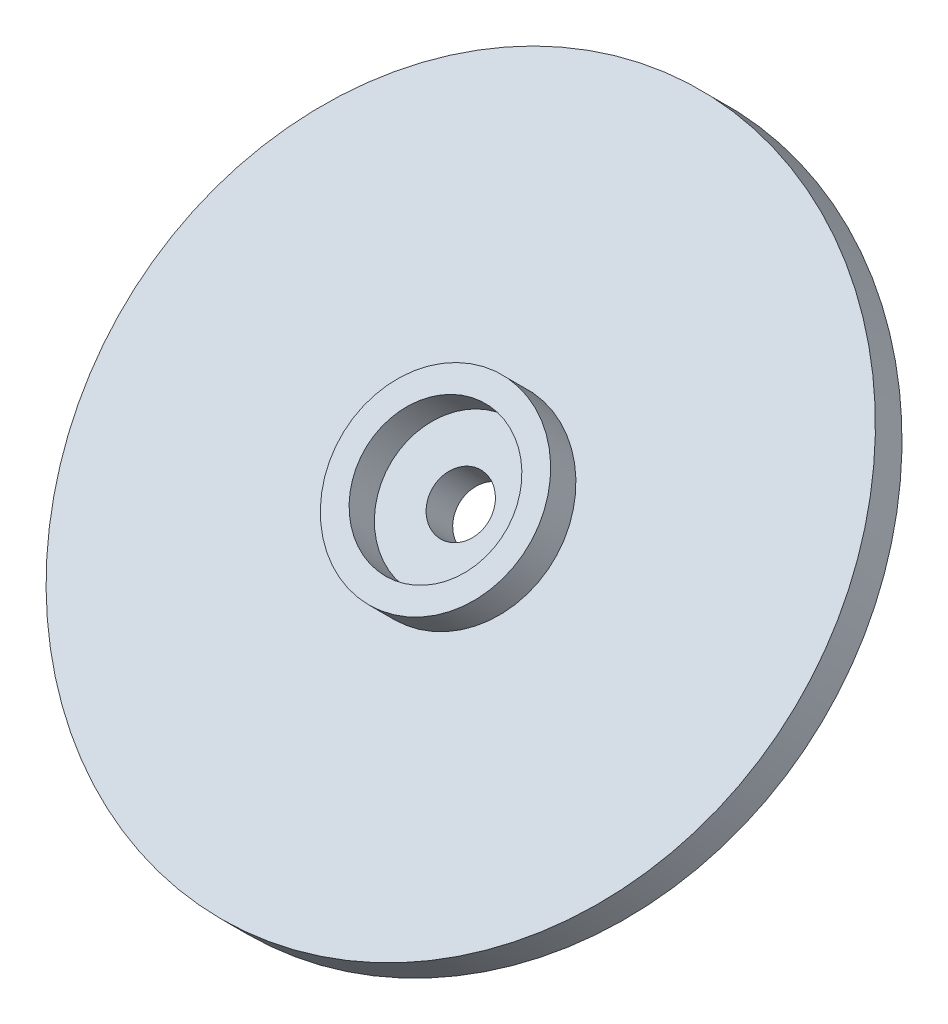
SolidWorks part; units mm, degrees
ref_plane "Front" through (0, 0, 0) normal (0, 0, 1) x (1, 0, 0)
ref_plane "Top" through (0, 0, 0) normal (0, 1, 0) x (1, 0, 0)
ref_plane "Right" through (0, 0, 0) normal (1, 0, 0) x (0, 0, -1)
sketch "Skizze1" plane through (0, 0, 0) normal (0, 1, 0) x (1, 0, 0)
  line L0 (-40.2583, -18.6594) -> (58.6621, -18.6594)
ref_plane "Ebene1" through (0, 9.3297, 9.3297) normal (0, 0.7071, 0.7071) x (1, 0, 0)
sketch "Skizze2" plane through (0, 9.3297, 9.3297) normal (0, 0.7071, 0.7071) x (1, 0, 0)
  line L1 (-127.2792, 52.7208) -> (127.2792, 52.7208) construction
  line L2 (-127.2792, 52.7208) -> (-127.2792, 307.2792) construction
  line L3 (-127.2792, 307.2792) -> (127.2792, 307.2792) construction
  line L4 (127.2792, 52.7208) -> (127.2792, 307.2792) construction
  line L5 (-127.2792, 52.7208) -> (127.2792, 307.2792) construction
  line L6 (-127.2792, 307.2792) -> (127.2792, 52.7208) construction
  circle A0 centre (0, 180) radius 180
  circle A1 centre (0, 180) radius 15.05
  dimension "D1" = 360
  dimension "D2" = 30.1
extrude "Aufsatz-Linear austragen1" add sketch "Skizze2" along normal blind 20
sketch "Skizze4" plane through (0, 9.3297, 9.3297) normal (0, -0.7071, -0.7071) x (1, 0, 0)
  line L0 (0, -180) -> (180, -180) construction
  line L1 (-87.2792, -52.7208) -> (-87.2792, -307.2792)
  line L2 (-127.2792, -307.2792) -> (-87.2792, -307.2792)
  line L3 (-127.2792, -307.2792) -> (-127.2792, -52.7208)
  line L4 (-127.2792, -52.7208) -> (-87.2792, -52.7208)
  line L5 (127.2792, -307.2792) -> (127.2792, -52.7208)
  line L6 (-127.2792, -307.2792) -> (127.2792, -52.7208) construction
  line L7 (-127.2792, -52.7208) -> (127.2792, -307.2792) construction
  line L8 (0, -180) -> (0, -52.7208) construction
  line L9 (87.2792, -52.7208) -> (87.2792, -307.2792)
  line L10 (87.2792, -52.7208) -> (127.2792, -52.7208)
  line L11 (87.2792, -307.2792) -> (127.2792, -307.2792)
  circle A0 centre (0, -180) radius 180 construction
  dimension "D1" = 40
extrude "Aufsatz-Linear austragen2" [suppressed] add sketch "Skizze4" along normal up to surface (65.915 mm away)
sketch "Skizze5" plane through (0, 23.4718, 23.4718) normal (0, 0.7071, 0.7071) x (1, 0, 0)
  circle A0 centre (0, 180) radius 37.5
  circle A1 centre (0, 180) radius 50
  dimension "D1" = 75
  dimension "D2" = 100
extrude "Aufsatz-Linear austragen3" add sketch "Skizze5" along normal blind 19 separate body
